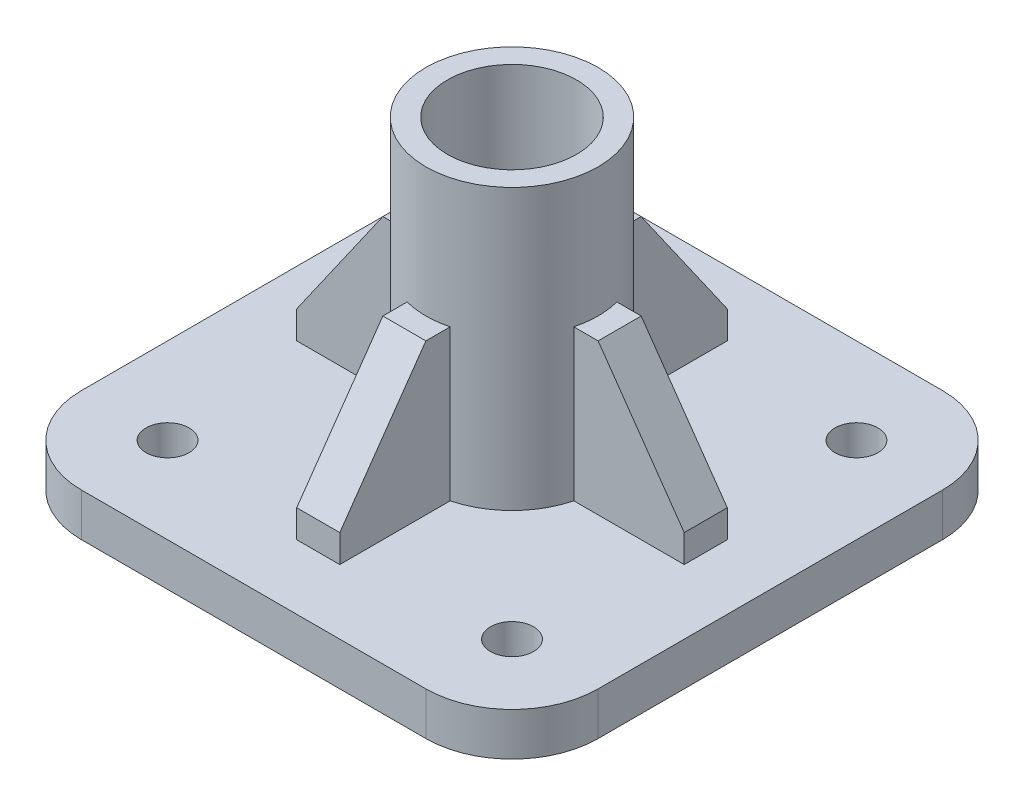
SolidWorks part; units mm, degrees
material "Plain Carbon Steel"
ref_plane "Front Plane" through (0, 0, 0) normal (0, 0, 1) x (1, 0, 0)
ref_plane "Top Plane" through (0, 0, 0) normal (0, 1, 0) x (1, 0, 0)
ref_plane "Right Plane" through (0, 0, 0) normal (1, 0, 0) x (0, 0, -1)
sketch "Sketch1" plane through (0, 0, 0) normal (0, 1, 0) x (1, 0, 0)
  line L1 (-60, 60) -> (60, 60)
  line L2 (-60, 60) -> (-60, -60)
  line L3 (-60, -60) -> (60, -60)
  line L4 (60, 60) -> (60, -60)
  line L5 (-60, 60) -> (60, -60) construction
  line L6 (-60, -60) -> (60, 60) construction
  point P0 (0, 0)
  dimension "D1" = 120
extrude "Boss-Extrude1" add sketch "Sketch1" along normal blind 10
sketch "Sketch2" plane through (0, 0, 0) normal (0, -1, 0) x (1, 0, 0)
  circle A0 centre (0, 0) radius 20
  dimension "D1" = 40
extrude "Boss-Extrude2" add sketch "Sketch2" against normal blind 75
sketch "Sketch3" plane through (0, 0, 0) normal (0, 0, 1) x (1, 0, 0)
  line L0 (-60, 10) -> (60, 10) construction
  line L1 (0, 10) -> (-45, 10)
  line L2 (0, 10) -> (0, 45)
  line L3 (0, 45) -> (-45, 45)
  line L4 (-45, 10) -> (-45, 45)
  dimension "D1" = 45
  dimension "D2" = 35
extrude "Boss-Extrude3" add sketch "Sketch3" along normal mid plane 10
chamfer "Chamfer1" distance 20 angle 55 1 edges at (-45, 45, 0)
pattern_circular "CirPattern1" count 4 over 360 about axis through (0, 0, 0) along (0, 1, 0) of "Boss-Extrude3", "Chamfer1"
sketch "Sketch4" plane through (0, 75, 0) normal (0, 1, 0) x (1, 0, 0)
  circle A0 centre (0, 0) radius 15
  circle A1 centre (0, 0) radius 20 construction
  dimension "D1" = 5
extrude "Cut-Extrude1" cut sketch "Sketch4" against normal through all
fillet "Fillet1" radius 20 4 edges at (60, 5, 60) (60, 5, -60) (-60, 5, 60) (-60, 5, -60)
hole_wizard "Ø10.0 (10) Diameter Hole1" positions "Sketch6" profile "Sketch5" hole size "Ø10.0" standard "Ansi Metric"
sketch "Sketch6" plane through (0, 10, 0) normal (0, 1, 0) x (-1, 0, 0)
  point P0 (40, -40)
  point P1 (40, 40)
  point P3 (-40, 40)
  point P5 (-40, -40)
sketch "Sketch5" plane through (-40, 10, -40) normal (1, 0, 0) x (0, 0, 1)
  line L0 (0, 0) -> (0, 13.0043)
  line L1 (0, 13.0043) -> (5, 10)
  line L2 (5, 10) -> (5, 0)
  line L5 (5, 0) -> (0, 0)
  line L10 (0, 13.0043) -> (-5, 10) construction
  line L11 (0, -6.35) -> (0, 107.95) construction
  dimension "Hole Dia." = 10
  dimension "Hole Depth" = 10
  dimension "Drill Angle" = 118
